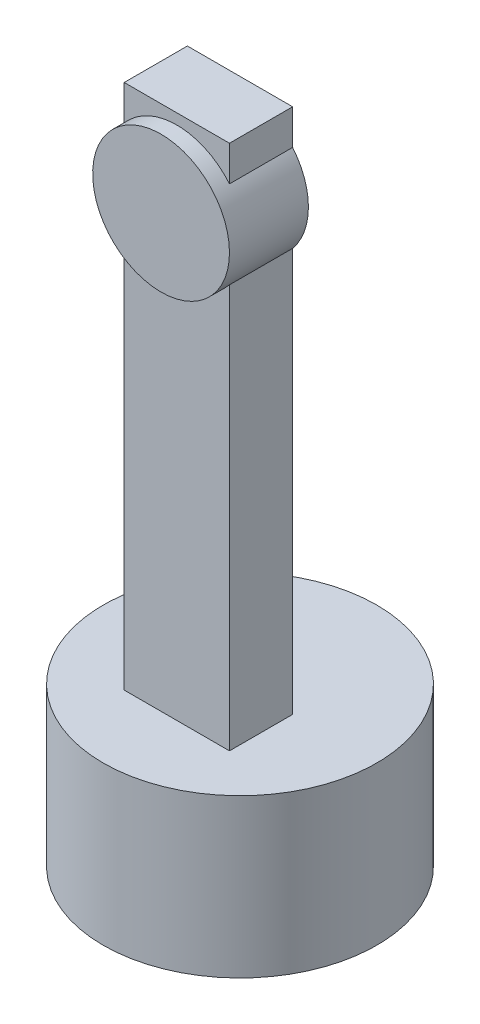
SolidWorks part; units mm, degrees
ref_plane "前视基准面" through (0, 0, 0) normal (0, 0, 1) x (1, 0, 0)
ref_plane "上视基准面" through (0, 0, 0) normal (0, 1, 0) x (1, 0, 0)
ref_plane "右视基准面" through (0, 0, 0) normal (1, 0, 0) x (0, 0, -1)
other "Configuration Table"
sketch "草图1" plane through (0, 0, 0) normal (0, 1, 0) x (1, 0, 0)
  circle A0 centre (0, 0) radius 26000
extrude "凸台-拉伸1" add sketch "草图1" along normal blind 30000
sketch "草图2" plane through (0, 0, 0) normal (0, 0, 1) x (1, 0, 0)
  line L1 (-10000, 26000) -> (10000, 26000)
  line L2 (-10000, 26000) -> (-10000, 130000)
  line L3 (-10000, 130000) -> (10000, 130000)
  line L4 (10000, 26000) -> (10000, 130000)
extrude "凸台-拉伸2" add sketch "草图2" along normal blind 12000
sketch "草图3" plane through (0, 0, 0) normal (0, 0, 1) x (1, 0, 0)
  circle A0 centre (0, 115000) radius 13000
extrude "凸台-拉伸3" add sketch "草图3" along normal blind 15000
